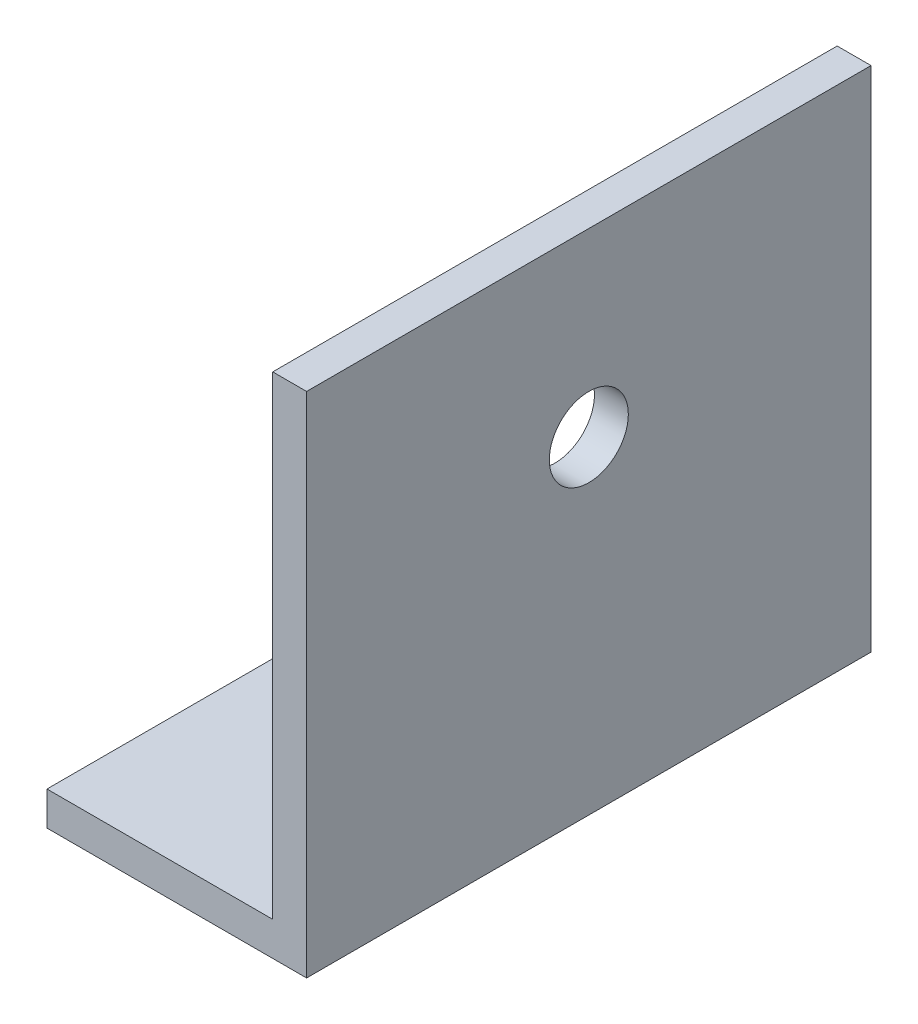
SolidWorks part; units mm, degrees
ref_plane "Front Plane" through (0, 0, 0) normal (0, 0, 1) x (1, 0, 0)
ref_plane "Top Plane" through (0, 0, 0) normal (0, 1, 0) x (1, 0, 0)
ref_plane "Right Plane" through (0, 0, 0) normal (1, 0, 0) x (0, 0, -1)
sketch "Sketch1" plane through (0, 0, 0) normal (0, 1, 0) x (1, 0, 0)
  line L1 (-10, -25) -> (10, -25)
  line L2 (-10, -25) -> (-10, 25)
  line L3 (-10, 25) -> (10, 25)
  line L4 (10, -25) -> (10, 25)
  line L5 (-10, -25) -> (10, 25) construction
  line L6 (-10, 25) -> (10, -25) construction
  point P0 (0, 0)
  dimension "D1" = 50
  dimension "D2" = 20
extrude "Boss-Extrude1" add sketch "Sketch1" along normal blind 3
sketch "Sketch2" plane through (10, 0, 0) normal (1, 0, 0) x (0, 0, -1)
  line L0 (25, 3) -> (25, 0) construction
  line L1 (-25, 0) -> (25, 0)
  line L2 (-25, 0) -> (-25, 45)
  line L3 (-25, 45) -> (25, 45)
  line L4 (25, 0) -> (25, 45)
  line L5 (0, 0) -> (0, 45) construction
  line L6 (-25, 3) -> (25, 3) construction
  circle A0 centre (0, 29) radius 3.5
  dimension "D3" = 7
  dimension "D1" = 45
  dimension "D2" = 26
extrude "Boss-Extrude2" add sketch "Sketch2" along normal blind 3
